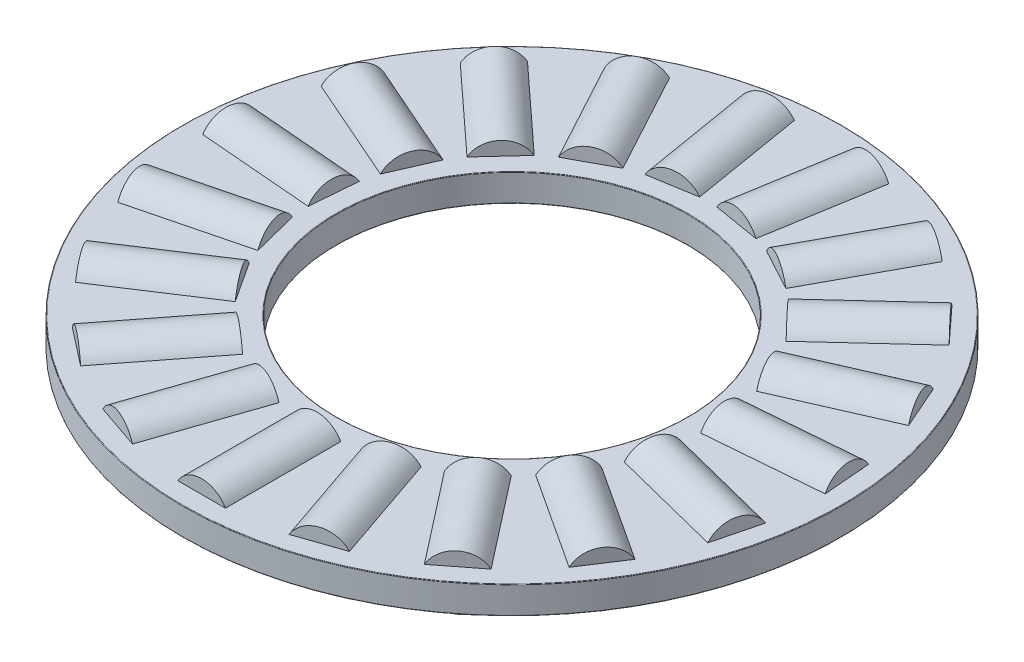
SolidWorks part; units mm, degrees
ref_plane "Front Plane" through (0, 0, 0) normal (0, 0, 1) x (1, 0, 0)
ref_plane "Top Plane" through (0, 0, 0) normal (0, 1, 0) x (1, 0, 0)
ref_plane "Right Plane" through (0, 0, 0) normal (1, 0, 0) x (0, 0, -1)
sketch "Sketch1" plane through (0, 0, 0) normal (1, 0, 0) x (0, 0, -1)
  line L0 (-11.9062, 0) -> (11.9062, 0) construction
  line L1 (0, -0.9922) -> (0, 0.9922) construction
  line L2 (-11.9063, 0.4961) -> (-6.35, 0.4961)
  line L3 (-11.9063, 0.4961) -> (-11.9063, -0.4961)
  line L4 (-11.9063, -0.4961) -> (-6.35, -0.4961)
  line L5 (-6.35, 0.4961) -> (-6.35, -0.4961)
  line L7 (-9.1281, 0.9922) -> (-9.1281, 0.4961) construction
  line L8 (-11.2117, 0.9922) -> (-7.0445, 0.9922) construction
  line L9 (-11.2117, 0.9922) -> (-11.2117, -0.9922) construction
  line L10 (-11.2117, -0.9922) -> (-7.0445, -0.9922) construction
  line L11 (-7.0445, 0.9922) -> (-7.0445, -0.9922) construction
  point P16 (-11.2117, 0)
  dimension "D1" = 4.1672
  dimension "OD" = 23.8125
  dimension "Shaft Dia" = 12.7
  dimension "Th" = 1.9844
  dimension "D2" = 0.9922
  dimension "D3" = 5.5562
revolve "Revolve1" add sketch "Sketch1" angle 360 about L1
sketch "Sketch3" plane through (0, 0, 0) normal (1, 0, 0) x (0, 0, -1)
  line L0 (-11.2117, 0.9922) -> (-11.2117, -0.9922) construction
  line L1 (-11.2117, 0) -> (-7.0445, 0)
  line L2 (-11.2117, 0) -> (-11.2117, 0.9922)
  line L3 (-11.2117, 0.9922) -> (-7.0445, 0.9922)
  line L4 (-7.0445, 0) -> (-7.0445, 0.9922)
revolve "Cut-Revolve1" cut sketch "Sketch3" angle 360 about L1
sketch "Sketch2" plane through (0, 0, 0) normal (1, 0, 0) x (0, 0, -1)
  line L1 (-11.2117, 0) -> (-7.0445, 0)
  line L2 (-11.2117, 0) -> (-11.2117, 0.9922)
  line L3 (-11.2117, 0.9922) -> (-7.0445, 0.9922)
  line L4 (-7.0445, 0) -> (-7.0445, 0.9922)
revolve "Revolve2" add sketch "Sketch2" angle 360 about L1
ref_axis "Axis1" through (0, 0.9922, 0) along (0, -1, 0)
pattern_circular "CirPattern1" count 19 every 18.947 about axis through (0, 0.9922, 0) along (0, -1, 0) of bodies 187 411
pattern_circular "CirPattern2" count 19 every 18.947 about axis through (0, 0, 0) along (0, 1, 0) of "Cut-Revolve1"
sketch "Sketch4" plane through (0, 0, 0) normal (1, 0, 0) x (0, 0, -1)
  line L0 (-11.9063, 0.4961) -> (-11.9063, -0.4961) construction
  line L1 (-11.9062, 9.1091) -> (-6.35, 9.1091)
  line L2 (-11.9062, 9.1091) -> (-11.9062, 9.9219)
  line L3 (-11.9062, 9.9219) -> (-6.35, 9.9219)
  line L4 (-6.35, 9.1091) -> (-6.35, 9.9219)
  line L5 (-11.9062, -9.9219) -> (-6.35, -9.9219)
  line L6 (-11.9062, -9.9219) -> (-11.9062, -9.1091)
  line L7 (-11.9062, -9.1091) -> (-6.35, -9.1091)
  line L8 (-6.35, -9.9219) -> (-6.35, -9.1091)
  line L10 (-6.35, 0.4961) -> (-6.35, -0.4961) construction
  line L11 (0, 0) -> (-11.9062, 0) construction
  line L12 (-11.9062, 0) -> (11.9062, 0) construction
  line L13 (0, -0.9922) -> (0, 0.9922) construction
  dimension "Ht" = 19.8438
  dimension "Washer Th" = 0.8128
  dimension "Washer ID" = 12.7
  dimension "Washer OD" = 23.8125
revolve "Revolve3" [suppressed] add sketch "Sketch4" angle 360 about L1
fillet "Fillet1" [suppressed] radius 0.0198
fillet "Fillet2" radius 0.0198 4 edges at (0, -0.4961, -6.35) (0, 0.4961, -6.35) (0, -0.4961, -11.9063) (0, 0.4961, -11.9063)
fillet "Fillet3" [suppressed] radius 0.0198
equation "\"D2@Sketch1\" = \"Th@Sketch1\"*.5"
equation "\"D1@Fillet1\" = \"Th@Sketch1\"*.01"
equation "\"D1@Fillet2\" = \"D1@Fillet1\""
equation "\"D1@Fillet3\" = \"D1@Fillet1\""
equation "\"D1@Sketch1\" = \"D3@Sketch1\"*.75"
equation "\"Angle@CirPattern1\" = 360/\"Rollers@CirPattern1\""
equation "\"Rollers@CirPattern1\" = \"OD@Sketch1\"*20"
equation "\"D1@CirPattern2\" = \"Rollers@CirPattern1\""
equation "\"D2@CirPattern2\" = \"Angle@CirPattern1\""
equation "\"Ht@Sketch4\" = \"Th@Sketch1\"*10"
